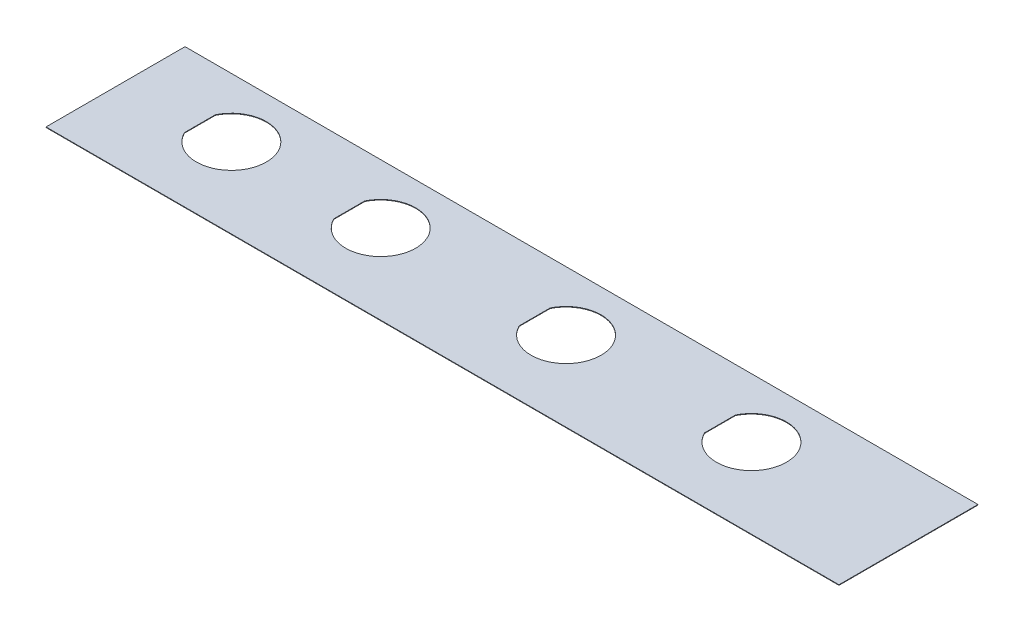
SolidWorks part; units mm, degrees
ref_plane "Front Plane" through (0, 0, 0) normal (0, 0, 1) x (1, 0, 0)
ref_plane "Top Plane" through (0, 0, 0) normal (0, 1, 0) x (1, 0, 0)
ref_plane "Right Plane" through (0, 0, 0) normal (1, 0, 0) x (0, 0, -1)
sketch "Sketch1" plane through (0, 0, 0) normal (0, 1, 0) x (1, 0, 0)
  line L1 (-77, 13.5) -> (77, 13.5)
  line L2 (-77, 13.5) -> (-77, -13.5)
  line L3 (-77, -13.5) -> (77, -13.5)
  line L4 (77, 13.5) -> (77, -13.5)
  line L5 (-77, 13.5) -> (77, -13.5) construction
  line L6 (-77, -13.5) -> (77, 13.5) construction
  point P0 (0, 0)
  dimension "D1" = 154
  dimension "D2" = 27
extrude "Boss-Extrude1" add sketch "Sketch1" along normal blind 0.1
sketch "Sketch2" plane through (0, 0.1, 0) normal (0, 1, 0) x (1, 0, 0)
  line L2 (2.4, 5.005) -> (2.4, -1.005)
  line L3 (-65.275, 37.7995) -> (-65.275, -44.9406) construction
  line L4 (65.275, 37.7995) -> (65.275, -50.8521) construction
  line L6 (38.4, 5.005) -> (38.4, -1.005)
  line L10 (-33.6, 5.005) -> (-33.6, -1.005)
  line L24 (-62.6, 5.005) -> (-62.6, -1.005)
  line L25 (77, 13.5) -> (-77, 13.5) construction
  circle A3 centre (44.5, 2) radius 8.75 construction
  arc A6 (-62.6, -1.005) -> (-62.6, 5.005) centre (-56.5, 2) ccw
  circle A9 centre (-27.5, 2) radius 8.75 construction
  arc A12 (-33.6, -1.005) -> (-33.6, 5.005) centre (-27.5, 2) ccw
  arc A15 (38.4, -1.005) -> (38.4, 5.005) centre (44.5, 2) ccw
  circle A18 centre (8.5, 2) radius 8.75 construction
  arc A21 (2.4, -1.005) -> (2.4, 5.005) centre (8.5, 2) ccw
  circle A31 centre (-56.5, 2) radius 8.75 construction
  dimension "D4" = 6.1
  dimension "D10" = 17.5
  dimension "D8" = 36
  dimension "D14" = 11.5
  dimension "D2" = 6.1
  dimension "D3" = 6.1
  dimension "D5" = 6.1
  dimension "D6" = 130.55
  dimension "D7" = 65.275
  dimension "D15" = 44.5
  dimension "D16" = 27.5
  dimension "D17" = 56.5
extrude "Cut-Extrude1" cut sketch "Sketch2" against normal through all
